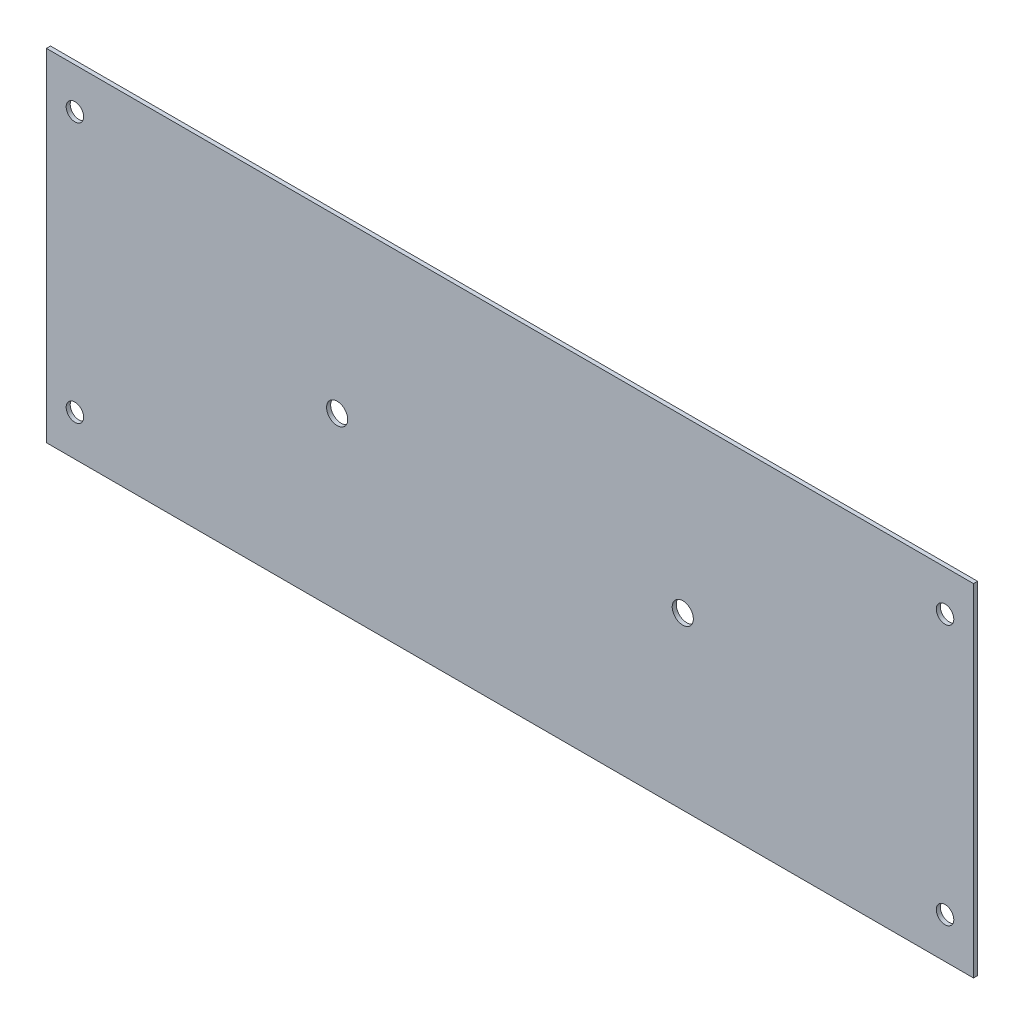
SolidWorks part; units mm, degrees
ref_plane "Спереди" through (0, 0, 0) normal (0, 0, 1) x (1, 0, 0)
ref_plane "Сверху" through (0, 0, 0) normal (0, 1, 0) x (1, 0, 0)
ref_plane "Справа" through (0, 0, 0) normal (1, 0, 0) x (0, 0, -1)
sketch "Эскиз1" plane through (0, 0, 0) normal (0, 0, 1) x (1, 0, 0)
  line L0 (0, 0) -> (58.1726, 0) construction
  line L1 (0, 0) -> (0, 47.3035) construction
  line L2 (-42.5, 0) -> (42.5, 0) construction
  line L3 (-114, -42) -> (114, -42)
  line L4 (-114, -42) -> (-114, 42)
  line L5 (-114, 42) -> (114, 42)
  line L6 (114, -42) -> (114, 42)
  circle A0 centre (-42.5, 0) radius 2.6
  circle A1 centre (42.5, 0) radius 2.6
  circle A8 centre (107, 32) radius 2.15
  circle A9 centre (-107, 32) radius 2.15
  circle A10 centre (-107, -32) radius 2.15
  circle A11 centre (107, -32) radius 2.15
  dimension "D4" = 85
  dimension "D5" = 42
  dimension "D6" = 71.5
  dimension "D14" = 4.3
  dimension "D15" = 10
  dimension "D16" = 7
  dimension "D7" = 5.2
  dimension "D3" = 64
  dimension "D1" = 84
  dimension "D2" = 228
extrude "Вытянуть1" add sketch "Эскиз1" along normal blind 1
